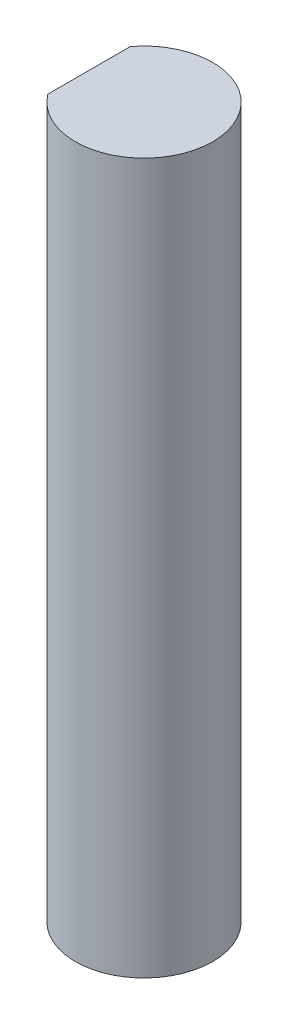
SolidWorks part; units mm, degrees
ref_plane "Front Plane" through (0, 0, 0) normal (0, 0, 1) x (1, 0, 0)
ref_plane "Top Plane" through (0, 0, 0) normal (0, 1, 0) x (1, 0, 0)
ref_plane "Right Plane" through (0, 0, 0) normal (1, 0, 0) x (0, 0, -1)
sketch "Sketch2" plane through (0, 0, 0) normal (0, 1, 0) x (1, 0, 0)
  line L0 (-2.4, 1.8) -> (-2.4, -1.8)
  arc A0 (-2.4, -1.8) -> (-2.4, 1.8) centre (0, 0) ccw
  dimension "D1" = 6
  dimension "D2" = 2.4
extrude "Boss-Extrude1" add sketch "Sketch2" along normal blind 31
equation "\"D2@Sketch2\"=(\"D1@Sketch2\"/2)*0.8"
